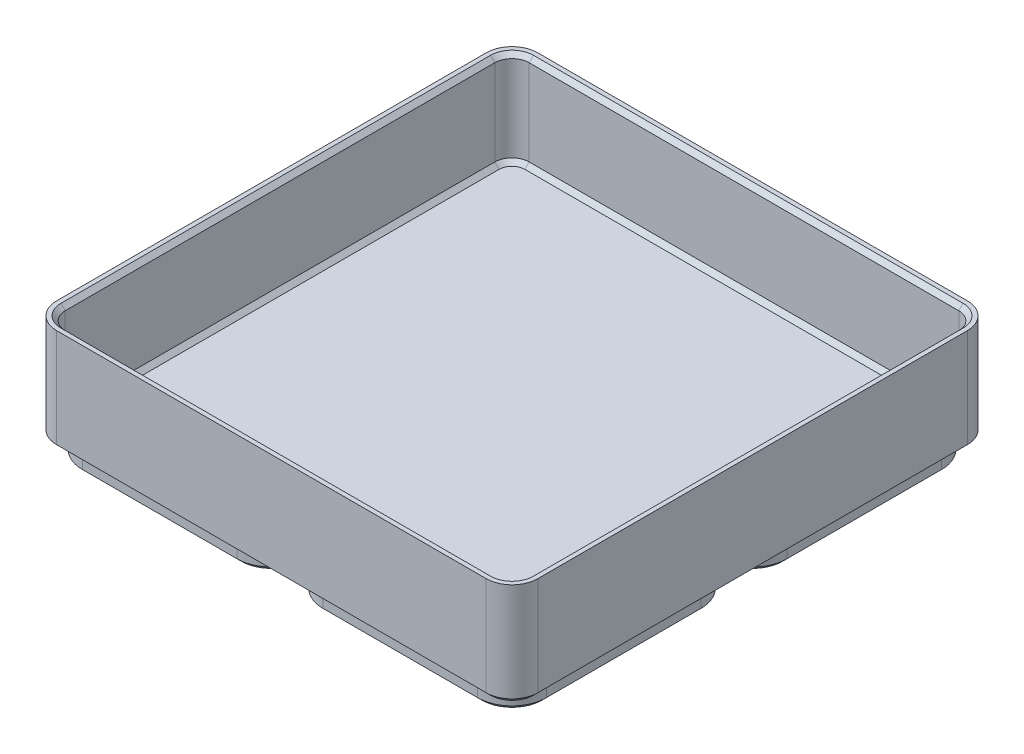
SolidWorks part; units mm, degrees
ref_plane "Front Plane" through (0, 0, 0) normal (0, 0, 1) x (1, 0, 0)
ref_plane "Top Plane" through (0, 0, 0) normal (0, 1, 0) x (1, 0, 0)
ref_plane "Right Plane" through (0, 0, 0) normal (1, 0, 0) x (0, 0, -1)
sketch "Sketch5" plane through (0, 0, 0) normal (0, 1, 0) x (1, 0, 0)
  line L1 (-22.5, -32.5) -> (22.5, -32.5)
  line L2 (-32.5, -22.5) -> (-32.5, 22.5)
  line L3 (-22.5, 32.5) -> (22.5, 32.5)
  line L4 (32.5, -22.5) -> (32.5, 22.5)
  line L5 (-32.5, -32.5) -> (32.5, 32.5) construction
  line L6 (-32.5, 32.5) -> (32.5, -32.5) construction
  arc A0 (-22.5, -32.5) -> (-32.5, -22.5) centre (-22.5, -22.5) cw
  arc A1 (22.5, -32.5) -> (32.5, -22.5) centre (22.5, -22.5) ccw
  arc A2 (22.5, 32.5) -> (32.5, 22.5) centre (22.5, 22.5) cw
  arc A3 (-32.5, 22.5) -> (-22.5, 32.5) centre (-22.5, 22.5) cw
  point P0 (0, 0)
  dimension "D3" = 10
  dimension "D1" = 65
  dimension "D2" = 65
extrude "Boss-Extrude4" add sketch "Sketch5" along normal blind 5
sketch "Sketch6" plane through (0, 5, 0) normal (0, 1, 0) x (1, 0, 0)
  line L1 (35, 35) -> (-35, 35)
  line L2 (35, 35) -> (35, -35)
  line L3 (35, -35) -> (-35, -35)
  line L4 (-35, 35) -> (-35, -35)
  line L5 (35, 35) -> (-35, -35) construction
  line L6 (35, -35) -> (-35, 35) construction
  point P0 (0, 0)
extrude "Boss-Extrude5" add sketch "Sketch6" along normal blind 30
sketch "Sketch8" plane through (0, 0, 0) normal (0, -1, 0) x (1, 0, 0)
  line L0 (-29.5711, 29.5711) -> (-22.5, 22.5)
  arc A0 (-22.5, 32.5) -> (-32.5, 22.5) centre (-22.5, 22.5) ccw construction
  circle A1 centre (-26.0355, 26.0355) radius 3
  circle A2 centre (26.0365, 26.0365) radius 3
  circle A3 centre (26.0375, -26.0355) radius 3
  circle A4 centre (-26.0345, -26.0365) radius 3
  point P8 (0, 0)
  point P15 (0.001, 0.001)
  point P18 (0.002, 0)
  point P21 (0.001, -0.001)
  point P22 (0.001, 0)
  dimension "D1" = 4
extrude "Cut-Extrude1" cut sketch "Sketch8" against normal blind 2 contours A3 | A2 | L0 A1 | L0 A1 | A4
mirror "Mirror1" about plane through (-35, 35, -35) normal (1, 0, 0) of bodies 112
mirror "Mirror2" about plane through (35, 35, 35) normal (0, 0, -1) of bodies 113
fillet "Fillet1" radius 7.5 4 edges at (35, 20, 105) (-105, 20, 105) (35, 20, -35) (-105, 20, -35)
sketch "Sketch11" plane through (0, 35, 0) normal (0, 1, 0) x (1, 0, 0)
  line L23 (32.5, -97.5) -> (32.5, 27.5)
  line L24 (-97.5, -102.5) -> (27.5, -102.5)
  line L25 (-102.5, 27.5) -> (-102.5, -97.5)
  line L26 (27.5, 32.5) -> (-97.5, 32.5)
  line L27 (32.5, -97.5) -> (32.5, 27.5)
  line L28 (-97.5, -102.5) -> (27.5, -102.5)
  line L29 (-102.5, 27.5) -> (-102.5, -97.5)
  line L30 (27.5, 32.5) -> (-97.5, 32.5)
  arc A21 (32.5, 27.5) -> (27.5, 32.5) centre (27.5, 27.5) ccw
  arc A22 (27.5, -102.5) -> (32.5, -97.5) centre (27.5, -97.5) ccw
  arc A23 (-102.5, -97.5) -> (-97.5, -102.5) centre (-97.5, -97.5) ccw
  arc A24 (-97.5, 32.5) -> (-102.5, 27.5) centre (-97.5, 27.5) ccw
  arc A25 (32.5, 27.5) -> (27.5, 32.5) centre (27.5, 27.5) ccw
  arc A26 (27.5, -102.5) -> (32.5, -97.5) centre (27.5, -97.5) ccw
  arc A27 (-102.5, -97.5) -> (-97.5, -102.5) centre (-97.5, -97.5) ccw
  arc A28 (-97.5, 32.5) -> (-102.5, 27.5) centre (-97.5, 27.5) ccw
  dimension "D1" = 2.5
extrude "Cut-Extrude2" cut sketch "Sketch11" against normal blind 27.5
chamfer "Chamfer1" distance 1.25 angle 45 16 edges at (31.0355, 7.5, 101.0355) (32.5, 7.5, 35) (-35, 7.5, 102.5) (31.0355, 7.5, -31.0355) (-101.0355, 7.5, 101.0355) (-35, 7.5, -32.5) (-102.5, 7.5, 35) (-101.0355, 7.5, -31.0355) (31.0355, 35, 101.0355) (32.5, 35, 35) (-35, 35, 102.5) (31.0355, 35, -31.0355) (-101.0355, 35, 101.0355) (-35, 35, -32.5) (-102.5, 35, 35) (-101.0355, 35, -31.0355)
chamfer "Chamfer2" distance 1.25 angle 45 40 edges at (32.5, 0, 0) (29.5711, 0, 29.5711) (0, 0, 32.5) (-29.5711, 0, 29.5711) (-29.5711, 0, 40.4289) (0, 0, 37.5) (29.5711, 0, 40.4289) (32.5, 0, 70) (29.5711, 0, 99.5711) (0, 0, 102.5) (-29.5711, 0, 99.5711) (-32.5, 0, 70) (-40.4289, 0, 40.4289) (-70, 0, 37.5) (-99.5711, 0, 40.4289) (-102.5, 0, 70) (-99.5711, 0, 99.5711) (-70, 0, 102.5) (-40.4289, 0, 99.5711) (-37.5, 0, 70) (-35, 5, -35) (35, 5, 35) (-35, 5, 105) (-105, 5, 35) (-102.8033, 5, 102.8033) (-102.8033, 5, -32.8033) (32.8033, 5, 102.8033) (32.8033, 5, -32.8033) (-40.4289, 0, 29.5711) (-70, 0, 32.5) (-99.5711, 0, 29.5711) (-102.5, 0, 0) (-99.5711, 0, -29.5711) (-70, 0, -32.5) (-40.4289, 0, -29.5711) (-37.5, 0, 0) (-32.5, 0, 0) (-29.5711, 0, -29.5711) (0, 0, -32.5) (29.5711, 0, -29.5711)
